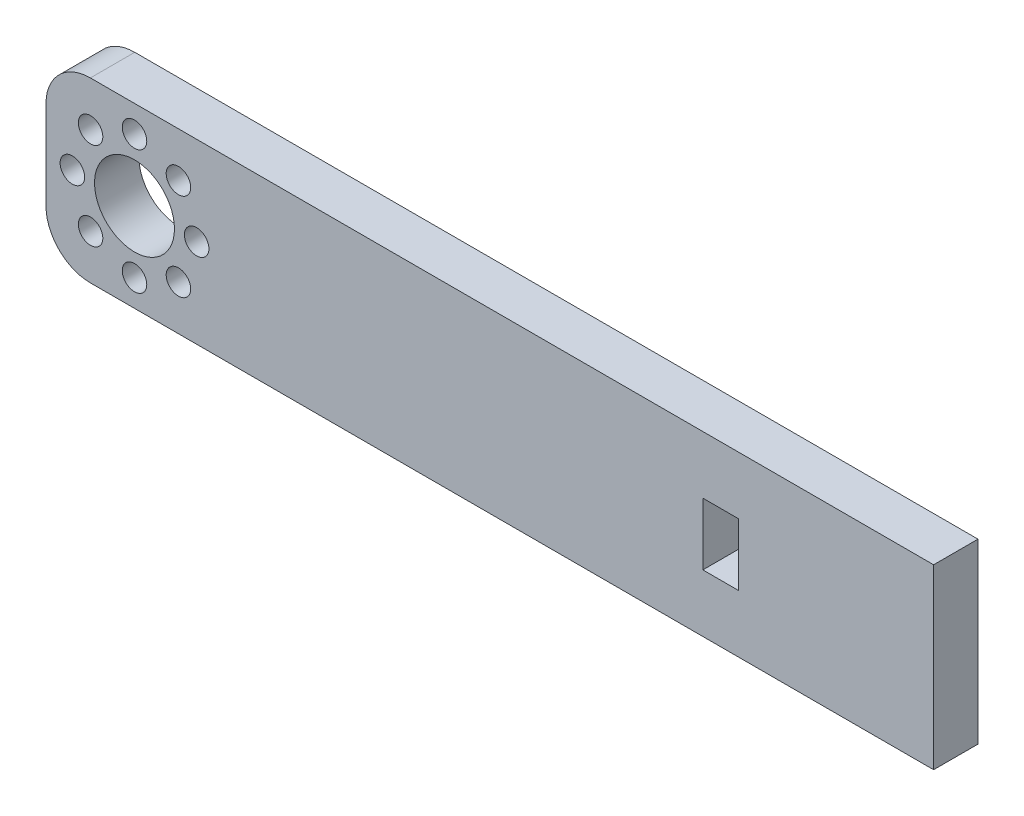
SolidWorks part; units mm, degrees
ref_plane "Front Plane" through (0, 0, 0) normal (0, 0, 1) x (1, 0, 0)
ref_plane "Top Plane" through (0, 0, 0) normal (0, 1, 0) x (1, 0, 0)
ref_plane "Right Plane" through (0, 0, 0) normal (1, 0, 0) x (0, 0, -1)
sketch "Sketch1" plane through (0, 0, 0) normal (0, 0, 1) x (1, 0, 0)
  line L1 (-60, 10) -> (60, 10)
  line L2 (-60, 10) -> (-60, -10)
  line L3 (-60, -10) -> (60, -10)
  line L4 (60, 10) -> (60, -10)
  point P0 (59.531, 10)
  point P20 (60, 10)
  point P23 (-60, -10)
  point P26 (-60, 10)
  dimension "D1" = 20
  dimension "D2" = 120
  dimension "D3" = 60
  dimension "D4" = 10
extrude "Boss-Extrude1" add sketch "Sketch1" along normal blind 5
fillet "Fillet1" radius 5 2 edges at (-60, 10, 2.5) (-60, -10, 2.5)
sketch "Sketch3" plane through (0, 0, 0) normal (0, 0, 1) x (1, 0, 0)
  line L0 (60, 10) -> (-55, 10) construction
  circle A0 centre (-50.029, 0) radius 4.5
  circle A1 centre (-50.029, 7) radius 1.3806
  circle A2 centre (-45.0793, 4.9497) radius 1.3806
  circle A3 centre (-43.029, 0) radius 1.3806
  circle A4 centre (-45.0793, -4.9497) radius 1.3806
  circle A5 centre (-50.029, -7) radius 1.3806
  circle A6 centre (-54.9788, -4.9497) radius 1.3806
  circle A7 centre (-57.029, 0) radius 1.3806
  circle A8 centre (-54.9788, 4.9497) radius 1.3806
  dimension "D1" = 9
  dimension "D4" = 2.7611
  dimension "D2" = 10
  dimension "D3" = 7
  dimension "D5" = 8
extrude "Cut-Extrude2" cut sketch "Sketch3" along normal blind 17
sketch "Sketch4" plane through (0, 0, 0) normal (0, 0, 1) x (1, 0, 0)
  line L0 (-55, -10) -> (60, -10) construction
  line L1 (60, 10) -> (40, 10)
  line L2 (60, 10) -> (60, -10)
  line L3 (60, -10) -> (40, -10)
  line L4 (40, 10) -> (40, -10)
  dimension "D1" = 20
extrude "Cut-Extrude3" cut sketch "Sketch4" along normal blind 20
sketch "Sketch6" plane through (0, 0, 5) normal (0, 0, 1) x (1, 0, 0)
  line L0 (40, 10) -> (-55, 10) construction
  line L1 (14, 3.5) -> (18, 3.5)
  line L2 (14, 3.5) -> (14, -3.5)
  line L3 (14, -3.5) -> (18, -3.5)
  line L4 (18, 3.5) -> (18, -3.5)
  line L5 (40, -10) -> (40, 10) construction
  point P4 (18, 0)
  dimension "D1" = 7
  dimension "D2" = 4
  dimension "D3" = 10
  dimension "D4" = 22
extrude "Cut-Extrude4" cut sketch "Sketch6" against normal blind 20
